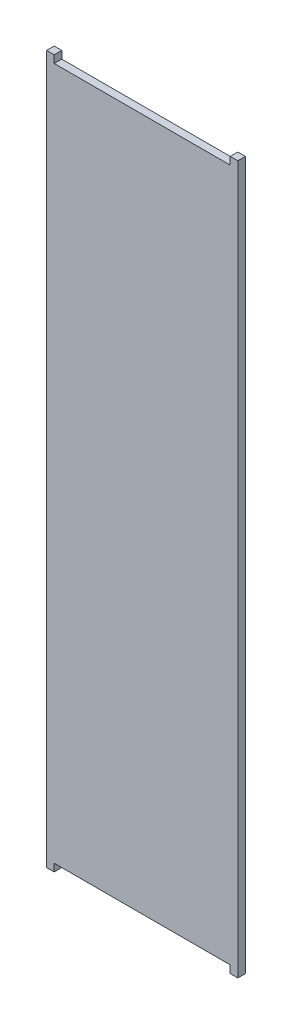
SolidWorks part; units mm, degrees
ref_plane "Front Plane" through (0, 0, 0) normal (0, 0, 1) x (1, 0, 0)
ref_plane "Top Plane" through (0, 0, 0) normal (0, 1, 0) x (1, 0, 0)
ref_plane "Right Plane" through (0, 0, 0) normal (1, 0, 0) x (0, 0, -1)
sketch "Sketch1" plane through (0, 0, 0) normal (0, 0, 1) x (1, 0, 0)
  line L0 (0.9075, 0) -> (-0.9075, 0) construction
  line L1 (-20.825, 77.1) -> (20.825, 77.1)
  line L2 (-20.825, 77.1) -> (-20.825, -77.1)
  line L3 (-20.825, -77.1) -> (20.825, -77.1)
  line L4 (20.825, 77.1) -> (20.825, -77.1)
  line L5 (0, -0.9075) -> (0, 0.9075) construction
  point P6 (20.825, 0)
  point P9 (0, 77.1)
  dimension "D1" = 154.2
  dimension "D2" = 41.65
extrude "Boss-Extrude1" add sketch "Sketch1" along normal blind 1.65
sketch "Sketch2" plane through (0, 0, 1.65) normal (0, 0, 1) x (1, 0, 0)
  line L0 (20.825, -77.1) -> (20.825, 77.1) construction
  line L1 (20.825, 75.45) -> (22.475, 75.45)
  line L2 (20.825, 75.45) -> (20.825, -75.45)
  line L3 (20.825, -75.45) -> (22.475, -75.45)
  line L4 (22.475, 75.45) -> (22.475, -75.45)
  line L5 (20.825, 77.1) -> (-20.825, 77.1) construction
  line L6 (-20.825, -77.1) -> (20.825, -77.1) construction
  line L7 (0, -0.9075) -> (0, 0.9075) construction
  line L8 (-22.475, 75.45) -> (-22.475, -75.45)
  line L9 (-20.825, -75.45) -> (-22.475, -75.45)
  line L10 (-20.825, 75.45) -> (-20.825, -75.45)
  line L11 (-20.825, 75.45) -> (-22.475, 75.45)
  dimension "D1" = 1.65
  dimension "D2" = 1.65
  dimension "D3" = 1.65
extrude "Boss-Extrude2" [suppressed] add sketch "Sketch2" against normal blind 1.65 separate body
sketch "Sketch3" plane through (0, 77.1, 0) normal (0, 1, 0) x (1, 0, 0)
  line L0 (20.825, 0) -> (-20.825, 0) construction
  line L1 (-19.175, 0) -> (19.175, 0)
  line L2 (-19.175, 0) -> (-19.175, -1.65)
  line L3 (-19.175, -1.65) -> (19.175, -1.65)
  line L4 (19.175, 0) -> (19.175, -1.65)
  line L5 (20.825, -1.65) -> (-20.825, -1.65) construction
  line L6 (20.825, -1.65) -> (20.825, 0) construction
  line L7 (-20.825, -1.65) -> (-20.825, 0) construction
  dimension "D1" = 1.65
  dimension "D2" = 1.65
extrude "Cut-Extrude1" cut sketch "Sketch3" against normal blind 1.65
mirror "Mirror1" about plane through (0, 0, 0) normal (0, 1, 0) of "Cut-Extrude1"
equation "\"Dinoskin scale\"= 1.8"
equation "\"pattern X\"= 3"
equation "\"Pattern Y\"= 9"
equation "\"Base Innerline\"= 0.34"
equation "\"lenght\"= 254"
equation "\"PCB Thickness\"= 1.65"
equation "\"Base Width\"= 4.5"
equation "\"Base Outerline\"= 1"
equation "\"Base Inner to Outer\"= 1"
equation "\"Dinoskin Outerline\"= \"Base Outerline\" * \"Dinoskin scale\""
equation "\"Dinoskin Innerline\"= \"Base Innerline\" * \"Dinoskin scale\""
equation "\"Dinoskin Width\"= \"Base Width\" * \"Dinoskin scale\""
equation "\"Dinoskin Inner to Outer\"= \"Base Inner to Outer\" * \"Dinoskin scale\""
equation "\"Diagonal dist\"= \"Dinoskin Width\" + ( ( \"Dinoskin Innerline\" + \"Dinoskin Outerline\" ) / 2 + \"Dinoskin Inner to Outer\" ) / cos ( 30 )"
equation "\"Dinoskin pattern Y\"= \"Diagonal dist\" * sin ( 30 )"
equation "\"Offset Y\"= 2 * \"Dinoskin pattern Y\""
equation "\"Diagonal dist 2\"= \"Dinoskin Width\" + ( ( \"Dinoskin Innerline\" + \"Dinoskin Outerline\" ) / 2 + 1 ) / cos ( 30 )"
equation "\"Dinoskin pattern X\"= \"Diagonal dist\" * cos ( 30 )"
equation "\"offset x\"= \"Dinoskin pattern X\" * 2"
equation "\"Pattern spacing X\"= \"offset x\" * ( \"pattern X\" - 0.5 ) / 2"
equation "\"Pattern spacing Y\"= \"Offset Y\" *  ( \"Pattern Y\" - 0.5 )  / 2 + 13"
equation "\"offset corner beams\" = 1"
equation "\"D1@Sketch1\"=(\"lenght\" * \"Lenght Ratio\" / 2) - 25 - \"lenght\" / 8 - \"PCB Thickness\" * 3"
equation "\"D2@Sketch1\"= 40 + \"PCB Thickness\""
equation "\"D1@Sketch2\"= \"PCB Thickness\""
equation "\"D2@Sketch2\"=\"PCB Thickness\""
equation "\"D3@Sketch2\"= \"PCB Thickness\""
equation "\"D1@Boss-Extrude2\"=  \"PCB Thickness\""
equation "\"D1@Sketch3\"=\"PCB Thickness\""
equation "\"D2@Sketch3\"=\"PCB Thickness\""
equation "\"D1@Cut-Extrude1\"=\"PCB Thickness\""
equation "\"D8@Sketch3\"=\"Dinoskin Inner to Outer\""
equation "\"D17@Sketch3\"=\"Dinoskin Width\""
equation "\"D6@Sketch3\"=\"Dinoskin Innerline\"/2"
equation "\"D3@Sketch3\"=\"Dinoskin Innerline\"/2"
equation "\"D20@Sketch3\"=\"Dinoskin Outerline\""
equation "\"D19@Sketch3\"=\"Dinoskin Outerline\""
equation "\"D15@Sketch3\"=\"Dinoskin Outerline\"/2"
equation "\"D14@Sketch3\"=\"Dinoskin Outerline\"/2"
equation "\"D10@Sketch3\"=\"Dinoskin Outerline\"/2"
equation "\"D16@Sketch3\"=\"Dinoskin Outerline\"/2"
equation "\"D3@LPattern1\"=\"Dinoskin pattern Y\""
equation "\"D1@Plane1\"=\"PCB Thickness\"/2"
equation "\"D2@LPattern2\"= \"pattern X\""
equation "\"D1@LPattern2\"=\"Pattern Y\""
equation "\"D4@LPattern1\"=\"Dinoskin pattern X\""
equation "\"D3@LPattern2\"= \"Offset Y\""
equation "\"D4@LPattern2\"= \"offset x\""
equation "\"D5@Sketch3\"= \"Pattern spacing X\""
equation "\"D7@Sketch3\"= \"Pattern spacing Y\""
equation "\"D1@Sketch5\"=\"PCB Thickness\""
equation "\"D3@Sketch5\"=\"lenght\" / 64"
equation "\"D5@Sketch5\"= \"offset corner beams\""
equation "\"D6@Sketch5\"=\"offset corner beams\""
equation "\"D1@Sketch6\"= \"lenght\" / 8 + \"PCB Thickness\" * 4"
equation "\"D2@Sketch6\"= \"PCB Thickness\""
equation "\"D3@DinoSkin diagonal pattern\" = \"Dinoskin pattern Y\""
equation "\"D2@Main Dinoskin Array\" = \"pattern X\""
equation "\"D1@Main Dinoskin Array\" = \"Pattern Y\""
equation "\"D4@DinoSkin diagonal pattern\" = \"Dinoskin pattern X\""
equation "\"D3@Main Dinoskin Array\" = \"Offset Y\""
equation "\"D4@Main Dinoskin Array\" = \"offset x\""
equation "\"D1@Sketch8\"=\"PCB Thickness\""
equation "\"D2@Sketch8\"=\"lenght\" / 64"
equation "\"D3@Sketch8\"=\"PCB Thickness\""
equation "\"D4@Sketch8\"= \"lenght\" / 64"
equation "\"D2@Sketch9\"=\"PCB Thickness\""
equation "\"D3@Sketch9\"=\"PCB Thickness\""
equation "\"D4@Sketch6\"=\"PCB Thickness\""
equation "\"D5@Sketch6\"=\"PCB Thickness\""
equation "\"D9@Sketch1\"= \"lenght\" * \"Lenght Ratio\"/2"
equation "\"Lenght Ratio\" = 1.7"
